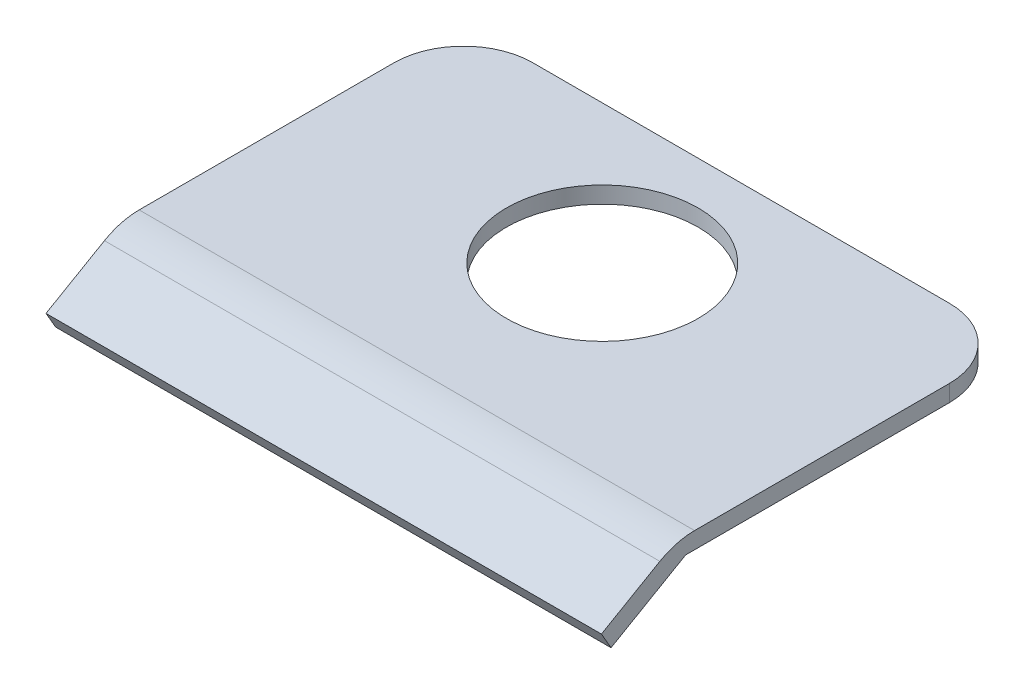
SolidWorks part; units mm, degrees
ref_plane "Front Plane" through (0, 0, 0) normal (0, 0, 1) x (1, 0, 0)
ref_plane "Top Plane" through (0, 0, 0) normal (0, 1, 0) x (1, 0, 0)
ref_plane "Right Plane" through (0, 0, 0) normal (1, 0, 0) x (0, 0, -1)
sketch "Sketch1" plane through (0, 0, 0) normal (0, 1, 0) x (1, 0, 0)
  line L0 (0, -1000) -> (0, 49000) construction
  line L1 (-25.4, 15.24) -> (25.4, 15.24)
  line L2 (-25.4, 15.24) -> (-25.4, -15.24)
  line L3 (-25.4, -15.24) -> (25.4, -15.24)
  line L4 (25.4, 15.24) -> (25.4, -15.24)
  line L5 (-25.4, 15.24) -> (25.4, -15.24) construction
  line L6 (-25.4, -15.24) -> (25.4, 15.24) construction
  circle A0 centre (0, 2.54) radius 8.763
  point P0 (0, 0)
  dimension "D3" = 17.526
  dimension "D1" = 50.8
  dimension "D2" = 30.48
  dimension "D4" = 12.7
extrude "Boss-Extrude1" add sketch "Sketch1" along normal blind 1.524
sketch "Sketch2" plane through (-25.4, 0, 0) normal (-1, 0, 0) x (0, 0, 1)
  line L0 (15.24, 0) -> (16.1199, 1.524) construction
  line L1 (15.24, 0) -> (22.0591, -3.937)
  line L2 (16.1199, 1.524) -> (22.939, -2.413)
  line L3 (22.0591, -3.937) -> (22.939, -2.413)
  line L4 (19.5294, -0.4445) -> (18.6495, -1.9685) construction
  line L5 (15.6799, 0.762) -> (22.499, -3.175) construction
  line L6 (-15.24, 1.524) -> (15.24, 1.524) construction
  line L7 (15.24, 1.524) -> (16.1199, 1.524)
  line L8 (15.24, 1.524) -> (15.24, 0) construction
  line L9 (15.24, 1.524) -> (15.24, 0)
  point P114 (19.0895, -1.2065)
  dimension "D1" = 7.874
  dimension "D2" = 30
extrude "Boss-Extrude2" add sketch "Sketch2" against normal up to surface (50.8 mm away) up to face at (25.4, 0.762, 0)
fillet "Fillet1" radius 6.35 3 edges at (-25.4, 0.762, -15.24) (25.4, 0.762, -15.24) (0, 1.524, 16.1199)
